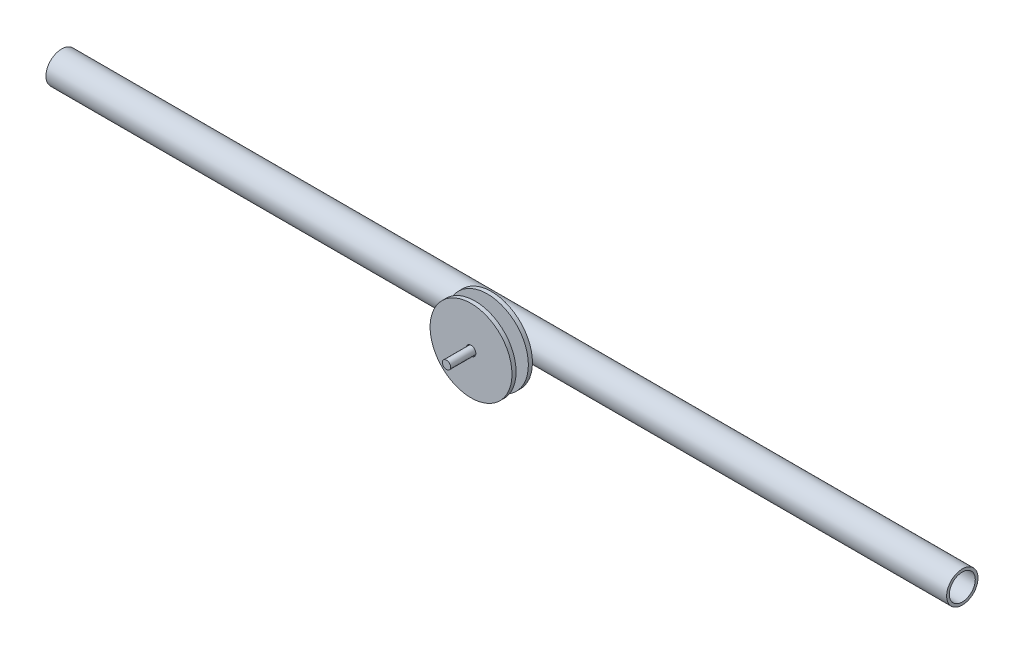
SolidWorks part; units mm, degrees
material "Acier non allié"
ref_plane "Front" through (0, 0, 0) normal (0, 0, 1) x (1, 0, 0)
ref_plane "Top" through (0, 0, 0) normal (0, 1, 0) x (1, 0, 0)
ref_plane "Right" through (0, 0, 0) normal (1, 0, 0) x (0, 0, -1)
sketch "Esquisse1" plane through (0, 0, 0) normal (1, 0, 0) x (0, 0, -1)
  circle A0 centre (0, 0) radius 5.75
  dimension "D1" = 11.5
extrude "Extru.-Mince1" add sketch "Esquisse1" along normal mid plane 330 thin thin type one direction reverse wall 1
sketch "Esquisse2" plane through (0, 0, 0) normal (0, 0, 1) x (1, 0, 0)
  circle A0 centre (0, 0) radius 1.5
  dimension "D1" = 3
extrude "Boss.-Extru.1" add sketch "Esquisse2" along normal blind 30 from offset 6 separate body offset against normal yes
sketch "Esquisse3" plane through (0, 0, 24) normal (0, 0, 1) x (1, 0, 0)
  circle A0 centre (0, 0) radius 15
  circle A1 centre (0, 0) radius 1.75
  dimension "D1" = 30
  dimension "D2" = 3.5
extrude "Boss.-Extru.2" add sketch "Esquisse3" against normal blind 1.5 from offset 9 separate body offset against normal yes
pattern_linear "Répétition linéaire1" count 2 spacing 6 along (0, 0, -1) of bodies 103
